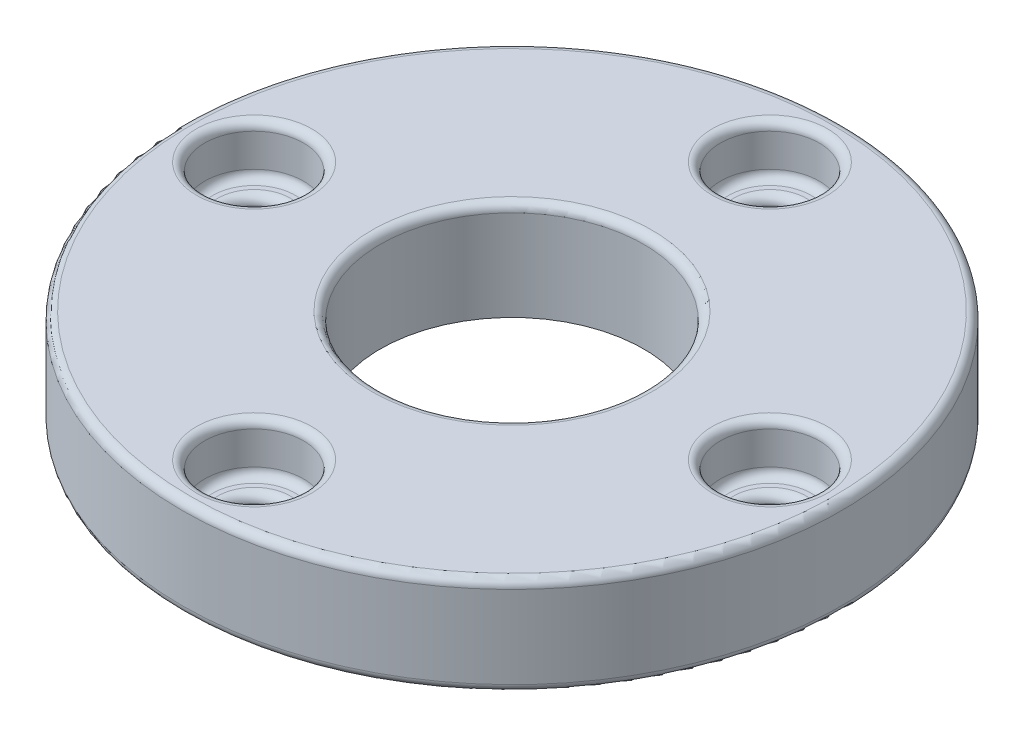
SolidWorks part; units mm, degrees
ref_plane "Front Plane" through (0, 0, 0) normal (0, 0, 1) x (1, 0, 0)
ref_plane "Top Plane" through (0, 0, 0) normal (0, 1, 0) x (1, 0, 0)
ref_plane "Right Plane" through (0, 0, 0) normal (1, 0, 0) x (0, 0, -1)
sketch "Sketch2" plane through (0, 0, 0) normal (0, 1, 0) x (1, 0, 0)
  circle A0 centre (0, 0) radius 20
  dimension "D1" = 40
extrude "Boss-Extrude1" add sketch "Sketch2" along normal blind 6
sketch "Sketch3" plane through (0, 6, 0) normal (0, 1, 0) x (1, 0, 0)
  circle A0 centre (0, 0) radius 8
  dimension "D1" = 16
extrude "Cut-Extrude1" cut sketch "Sketch3" against normal through all
sketch "Sketch4" plane through (0, 6, 0) normal (0, 1, 0) x (1, 0, 0)
  circle A0 centre (0, 0) radius 15.65 construction
  circle A1 centre (0, 15.65) radius 1.7
  circle A2 centre (-15.65, 0) radius 1.7
  circle A3 centre (0, -15.65) radius 1.7
  circle A4 centre (15.65, 0) radius 1.7
extrude "Cut-Extrude2" cut sketch "Sketch4" against normal through all
sketch "Sketch5" plane through (0, 6, 0) normal (0, 1, 0) x (1, 0, 0)
  circle A0 centre (0, 15.65) radius 3
  circle A1 centre (-15.65, 0) radius 3
  circle A2 centre (0, -15.65) radius 3
  circle A3 centre (15.65, 0) radius 3
extrude "Cut-Extrude3" cut sketch "Sketch5" against normal blind 3
fillet "Fillet1" radius 0.5 6 edges at (0, 6, 20) (0, 6, 8) (15.65, 6, 3) (0, 6, 18.65) (-15.65, 6, 3) (0, 6, -12.65)
fillet "Fillet2" radius 0.5 8 edges at (0, 3, 17.35) (0, 3, 18.65) (15.65, 3, 1.7) (15.65, 3, 3) (-15.65, 3, 1.7) (-15.65, 3, 3) (0, 3, -13.95) (0, 3, -12.65)
fillet "Fillet3" radius 0.5 1 edges at (0, 0, 20)
